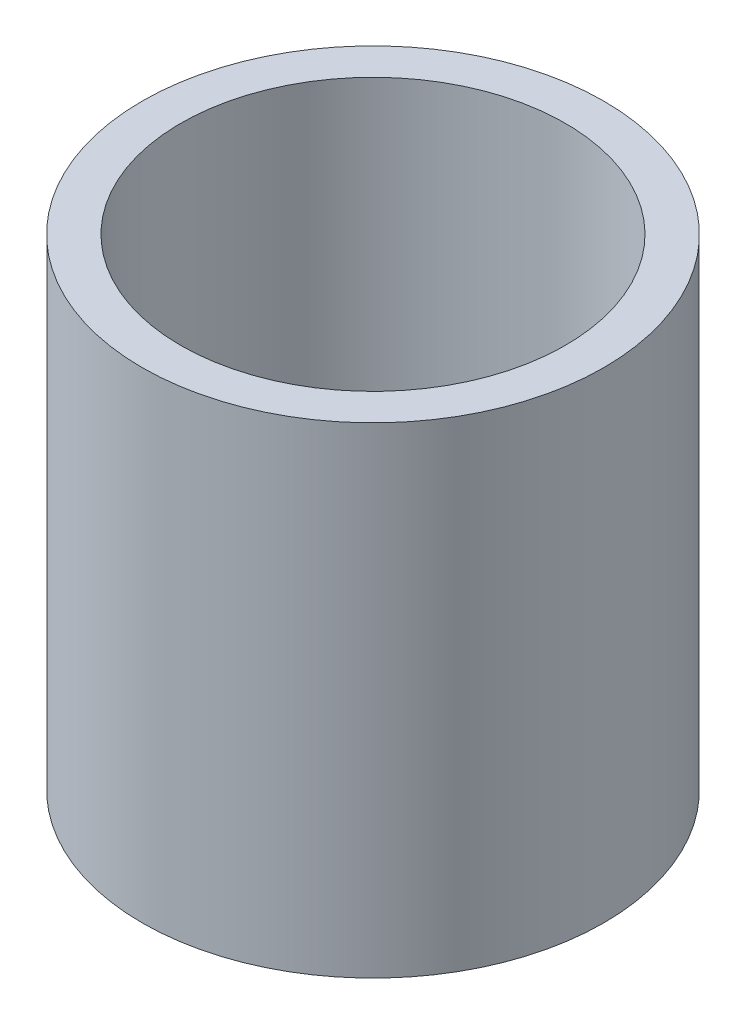
SolidWorks part; units mm, degrees
ref_plane "Front Plane" through (0, 0, 0) normal (0, 0, 1) x (1, 0, 0)
ref_plane "Top Plane" through (0, 0, 0) normal (0, 1, 0) x (1, 0, 0)
ref_plane "Right Plane" through (0, 0, 0) normal (1, 0, 0) x (0, 0, -1)
sketch "Sketch1" plane through (0, 0, 0) normal (0, 1, 0) x (1, 0, 0)
  circle A0 centre (0, 0) radius 10
  circle A1 centre (0, 0) radius 12
  dimension "D1" = 20
  dimension "D2" = 2
extrude "Boss-Extrude1" add sketch "Sketch1" along normal blind 25
